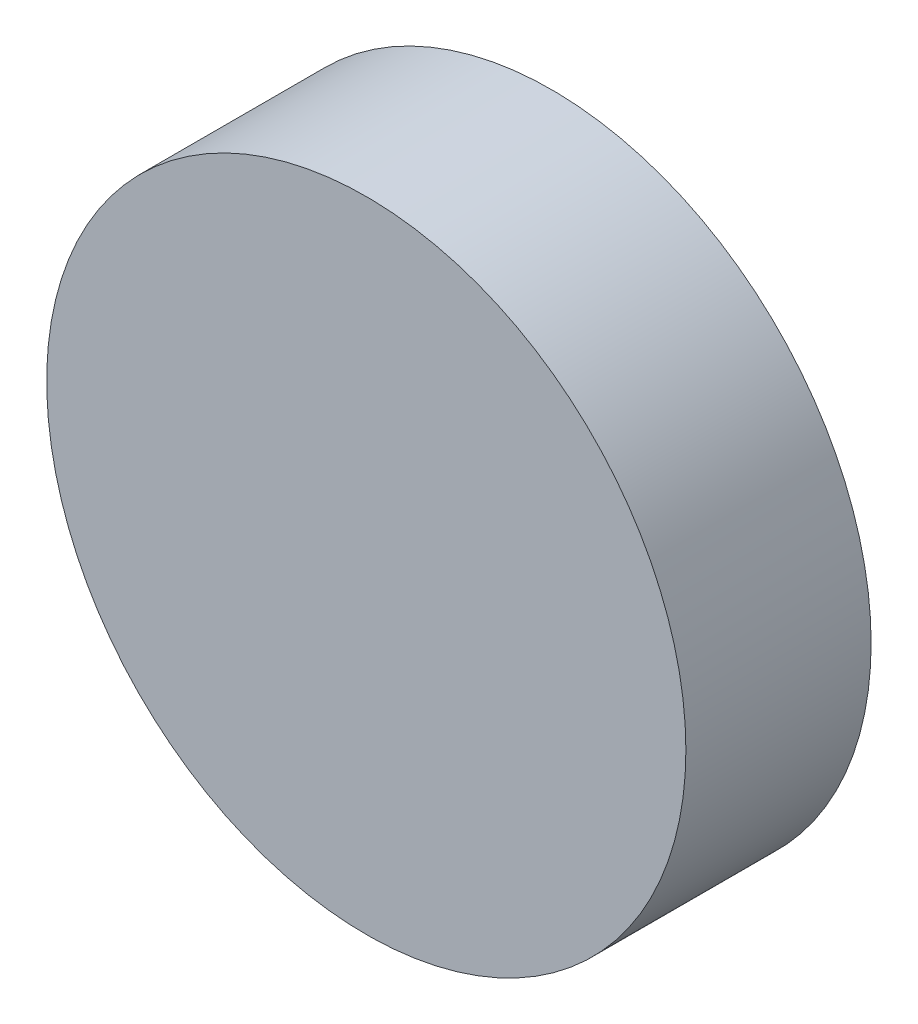
SolidWorks part; units mm, degrees
material "PLA imprimante 3D"
ref_plane "Plan de face" through (0, 0, 0) normal (0, 0, 1) x (1, 0, 0)
ref_plane "Plan de dessus" through (0, 0, 0) normal (0, 1, 0) x (1, 0, 0)
ref_plane "Plan de droite" through (0, 0, 0) normal (1, 0, 0) x (0, 0, -1)
other "Filament PLA"
sketch "Esquisse1" plane through (0, 0, 0) normal (0, 0, 1) x (1, 0, 0)
  circle A0 centre (0, 0) radius 25.8818
  dimension "D1" = 51.7635
extrude "Boss.-Extru.1" add sketch "Esquisse1" along normal blind 15
